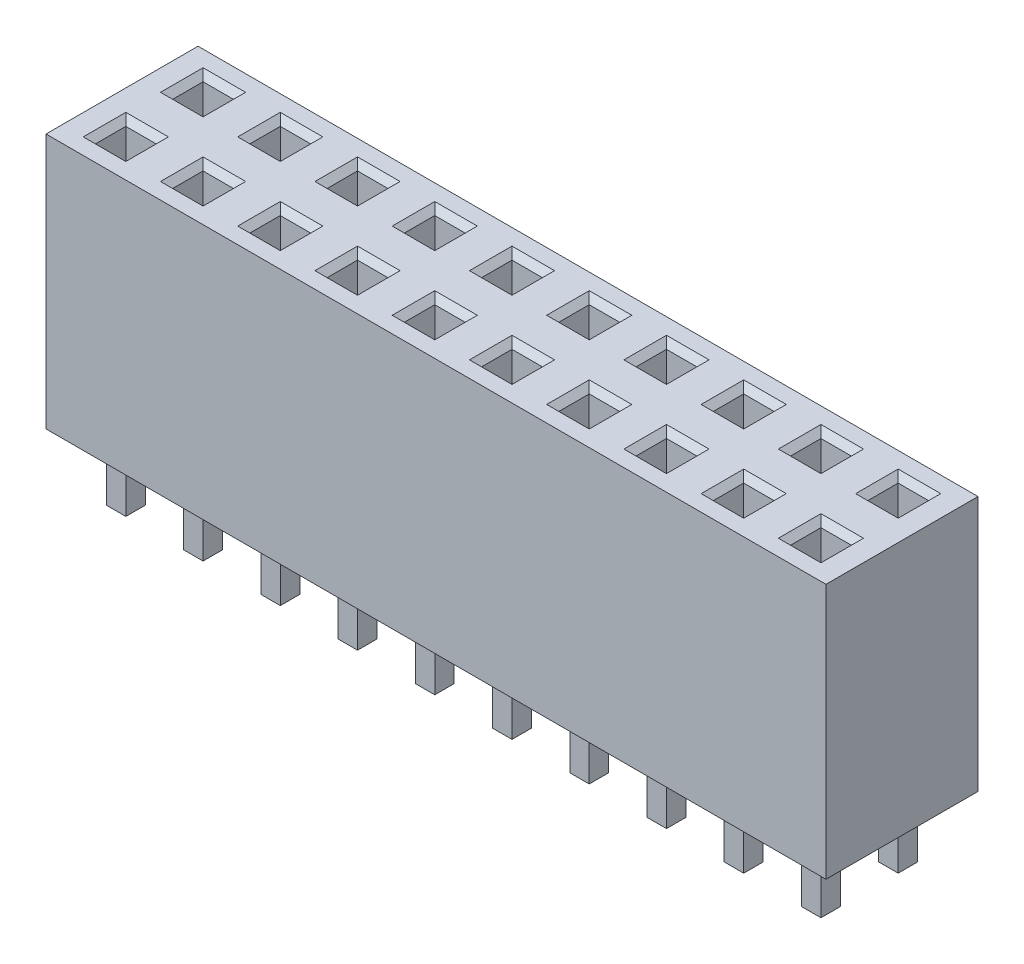
SolidWorks part; units mm, degrees
material "C (Графит)"
ref_plane "Спереди" through (0, 0, 0) normal (0, 0, 1) x (1, 0, 0)
ref_plane "Сверху" through (0, 0, 0) normal (0, 1, 0) x (1, 0, 0)
ref_plane "Справа" through (0, 0, 0) normal (1, 0, 0) x (0, 0, -1)
sketch "Эскиз1" plane through (0, 0, 0) normal (0, 1, 0) x (1, 0, 0)
  line L1 (-1.395, -2.5) -> (1.395, -2.5)
  line L2 (-1.395, -2.5) -> (-1.395, 2.5)
  line L3 (-1.395, 2.5) -> (1.395, 2.5)
  line L4 (1.395, -2.5) -> (1.395, 2.5)
  line L5 (-1.395, -2.5) -> (1.395, 2.5) construction
  line L6 (-1.395, 2.5) -> (1.395, -2.5) construction
  point P0 (0, 0)
  dimension "D1" = 5
  dimension "D2" = 2.79
extrude "Бобышка-Вытянуть1" add sketch "Эскиз1" along normal blind 8.4
sketch "Эскиз2" plane through (0, 8.4, 0) normal (0, 1, 0) x (1, 0, 0)
  line L0 (-1.395, 2.5) -> (-1.395, -2.5) construction
  line L1 (-0.5, 1.77) -> (0.5, 1.77)
  line L2 (-0.5, 1.77) -> (-0.5, 0.77)
  line L3 (-0.5, 0.77) -> (0.5, 0.77)
  line L4 (0.5, 1.77) -> (0.5, 0.77)
  line L5 (-0.5, 1.77) -> (0.5, 0.77) construction
  line L6 (-0.5, 0.77) -> (0.5, 1.77) construction
  line L7 (-1.395, 0) -> (-29.5201, 0) construction
  line L8 (0.5, -1.77) -> (0.5, -0.77)
  line L9 (-0.5, -0.77) -> (0.5, -0.77)
  line L10 (-0.5, -1.77) -> (-0.5, -0.77)
  line L11 (-0.5, -1.77) -> (0.5, -1.77)
  point P0 (0, 1.27)
  dimension "D1" = 1
  dimension "D2" = 1
  dimension "D3" = 1.395
  dimension "D4" = 1.27
extrude "Вырез-Вытянуть1" cut sketch "Эскиз2" against normal blind 8
chamfer "Фаска1" distance 0.2 angle 45 8 edges at (0.5, 8.4, -1.27) (0, 8.4, -0.77) (-0.5, 8.4, -1.27) (0, 8.4, -1.77) (0, 8.4, 1.77) (-0.5, 8.4, 1.27) (0, 8.4, 0.77) (0.5, 8.4, 1.27)
sketch "Эскиз3" plane through (0, 0, 0) normal (0, -1, 0) x (-1, 0, 0)
  line L0 (1.395, 2.5) -> (1.395, -2.5) construction
  line L1 (0.32, 0.95) -> (-0.32, 0.95)
  line L2 (0.32, 0.95) -> (0.32, 1.59)
  line L3 (0.32, 1.59) -> (-0.32, 1.59)
  line L4 (-0.32, 0.95) -> (-0.32, 1.59)
  line L5 (0.32, 0.95) -> (-0.32, 1.59) construction
  line L6 (0.32, 1.59) -> (-0.32, 0.95) construction
  line L7 (1.395, 0) -> (32.9327, 0) construction
  line L8 (0.32, -0.95) -> (-0.32, -0.95)
  line L9 (-0.32, -0.95) -> (-0.32, -1.59)
  line L10 (0.32, -1.59) -> (-0.32, -1.59)
  line L11 (0.32, -0.95) -> (0.32, -1.59)
  point P0 (0, 1.27)
  dimension "D1" = 0.64
  dimension "D2" = 0.64
  dimension "D3" = 1.395
  dimension "D4" = 2.54
extrude "Бобышка-Вытянуть2" add sketch "Эскиз3" along normal blind 2.29
chamfer "Фаска2" distance 0.2 angle 45 8 edges at (0, -2.29, -1.59) (-0.32, -2.29, -1.27) (0, -2.29, -0.95) (0.32, -2.29, -1.27) (0, -2.29, 1.59) (0.32, -2.29, 1.27) (0, -2.29, 0.95) (-0.32, -2.29, 1.27)
pattern_linear "Линейный массив1" count 10 spacing 2.54 along (1, 0, 0) of "Бобышка-Вытянуть1", "Вырез-Вытянуть1", "Фаска1", "Бобышка-Вытянуть2", "Фаска2"
